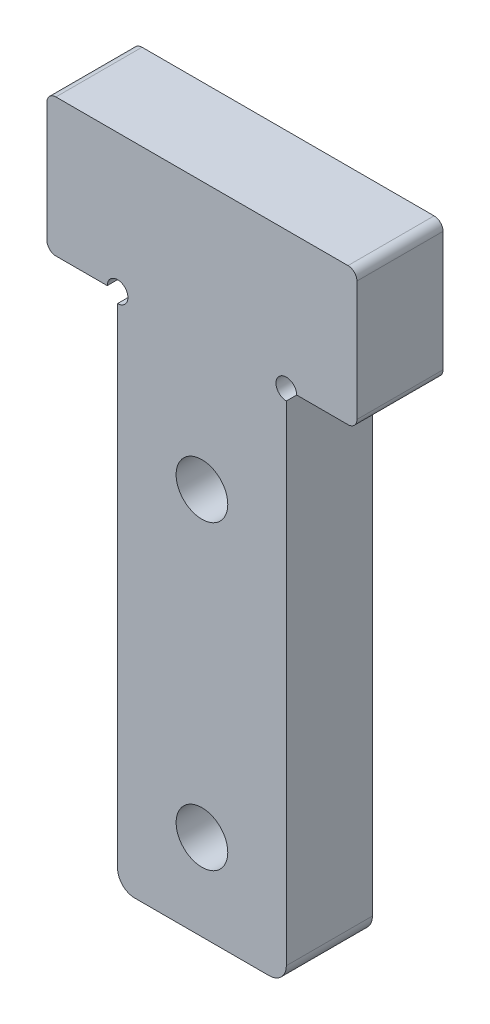
SolidWorks part; units mm, degrees
ref_plane "前视基准面" through (0, 0, 0) normal (0, 0, 1) x (1, 0, 0)
ref_plane "上视基准面" through (0, 0, 0) normal (0, 1, 0) x (1, 0, 0)
ref_plane "右视基准面" through (0, 0, 0) normal (1, 0, 0) x (0, 0, -1)
other "Configuration Table"
sketch "草图1" plane through (0, 0, 0) normal (0, 0, 1) x (1, 0, 0)
  line L0 (-4.9, -4.6) -> (-4.9, -33)
  line L1 (-8.4806, -4) -> (-5.9, -4)
  line L2 (-9, -3.4806) -> (-9, 3.4806)
  line L3 (-8.4806, 4) -> (8.4806, 4)
  line L4 (9, -3.4806) -> (9, 3.4806)
  line L5 (5.9, -4) -> (8.4806, -4)
  line L9 (-3.9, -34) -> (3.9, -34)
  line L12 (5.9, -4) -> (5.5, -4)
  line L13 (4.9, -4.6) -> (4.9, -33)
  line L16 (-5.9, -4) -> (-5.5, -4)
  line L18 (8.1859, -3.0528) -> (9, -4) construction
  line L19 (-4.9, -4) -> (-4.9, -4.1222)
  circle A0 centre (0, -11.5) radius 1.5
  circle A1 centre (0, -29) radius 1.5
  arc A2 (-4.9, -33) -> (-3.9, -34) centre (-3.9, -33) ccw
  arc A3 (3.9, -34) -> (4.9, -33) centre (3.9, -33) ccw
  arc A6 (-8.4806, -4) -> (-9, -3.4806) centre (-8.4806, -3.4806) cw
  arc A7 (8.4806, -4) -> (9, -3.4806) centre (8.4806, -3.4806) ccw
  arc A8 (8.4806, 4) -> (9, 3.4806) centre (8.4806, 3.4806) cw
  arc A9 (-9, 3.4806) -> (-8.4806, 4) centre (-8.4806, 3.4806) cw
  arc A11 (5.5, -4) -> (4.9, -4.6) centre (4.9, -4) ccw
  arc A12 (-4.9, -4.6) -> (-5.5, -4) centre (-4.9, -4) ccw
  point P0 (0, 0)
  point P6 (0, -8.4392)
  point P18 (-4.9, -34)
  point P21 (4.9, -34)
  point P24 (4.9, -4)
  point P29 (-9, -4)
  point P35 (9, 4)
  point P38 (0, 4)
  point P39 (0, -34)
  dimension "D8" = 3
  dimension "D9" = 3
  dimension "D10" = 1
  dimension "D11" = 1.2
  dimension "D12" = 1.2
  dimension "D1" = 18
  dimension "D2" = 9.8
  dimension "D3" = 8
  dimension "D4" = 4.9
  dimension "D5" = 30
  dimension "D6" = 7.5
  dimension "D7" = 17.5
  dimension "D13" = 4
extrude "凸台-拉伸1" add sketch "草图1" along normal blind 5
